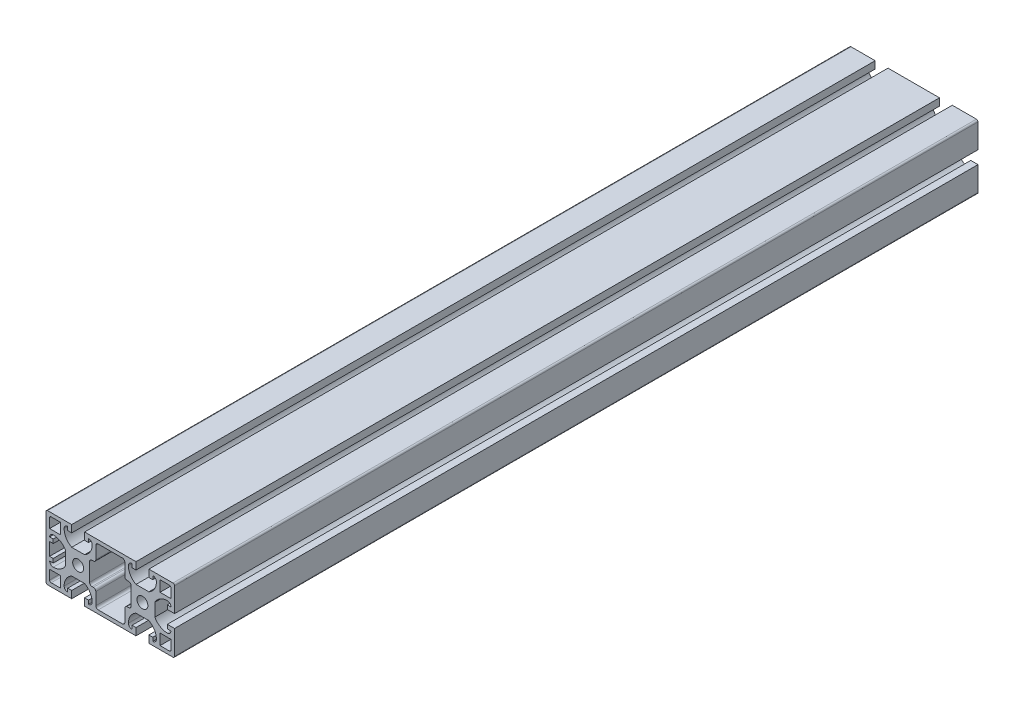
SolidWorks part; units mm, degrees
material "3.0255 (EN-AW 1350A)"
ref_plane "Płaszczyzna przednia" through (0, 0, 0) normal (0, 0, 1) x (1, 0, 0)
ref_plane "Płaszczyzna górna" through (0, 0, 0) normal (0, 1, 0) x (1, 0, 0)
ref_plane "Płaszczyzna prawa" through (0, 0, 0) normal (1, 0, 0) x (0, 0, -1)
sketch "Szkic1" plane through (0, 0, 0) normal (0, 0, 1) x (1, 0, 0)
  line L0 (0, 20) -> (0, -20) construction
  line L1 (-51.8865, 0) -> (40, 0) construction
  line L4 (-40, -19) -> (-40, 19)
  line L7 (-40, -20) -> (0, 0) construction
  line L8 (-40, 20) -> (40, -20) construction
  line L13 (20, 20) -> (20, 0) construction
  line L15 (24, 20) -> (24, 15.5)
  line L16 (24, 15.5) -> (26.4714, 15.5)
  line L21 (16, 15.5) -> (13.5286, 15.5)
  line L23 (16, 20) -> (13.5286, 20)
  line L24 (16, 20) -> (16, 15.5)
  line L25 (16, 7.75) -> (24, 7.75)
  line L26 (13.5286, 15.5) -> (13.5286, 17.75)
  line L27 (26.4714, 15.5) -> (26.4714, 17.75)
  line L28 (-24, 20) -> (-24, 15.5)
  line L29 (-26.4714, 15.5) -> (-26.4714, 17.75)
  line L30 (-24, 15.5) -> (-26.4714, 15.5)
  line L31 (-13.5286, 15.5) -> (-13.5286, 17.75)
  line L32 (-16, 15.5) -> (-13.5286, 15.5)
  line L33 (-16, 20) -> (-16, 15.5)
  line L34 (-16, 7.75) -> (-24, 7.75)
  line L35 (20, -20) -> (20, 0) construction
  line L36 (-40, -20) -> (0, 0) construction
  line L37 (-40, 20) -> (40, -20) construction
  line L38 (30.9714, -17.75) -> (36.75, -17.75)
  line L39 (-16, -7.75) -> (-24, -7.75)
  line L40 (-16, -20) -> (-16, -15.5)
  line L41 (-16, -15.5) -> (-13.5286, -15.5)
  line L42 (-13.5286, -15.5) -> (-13.5286, -17.75)
  line L43 (-24, -15.5) -> (-26.4714, -15.5)
  line L44 (-26.4714, -15.5) -> (-26.4714, -17.75)
  line L45 (-24, -20) -> (-24, -15.5)
  line L46 (26.4714, -15.5) -> (26.4714, -17.75)
  line L47 (13.5286, -15.5) -> (13.5286, -17.75)
  line L48 (16, -7.75) -> (24, -7.75)
  line L49 (16, -20) -> (16, -15.5)
  line L50 (16, -15.5) -> (13.5286, -15.5)
  line L51 (24, -15.5) -> (26.4714, -15.5)
  line L52 (24, -20) -> (24, -15.5)
  line L53 (40, -20) -> (0, 20) construction
  line L54 (35.5, 6.4714) -> (37.75, 6.4714)
  line L55 (35.5, 4) -> (35.5, 6.4714)
  line L56 (40, 4) -> (35.5, 4)
  line L57 (40, -4) -> (35.5, -4)
  line L58 (35.5, -4) -> (35.5, -6.4714)
  line L59 (35.5, -6.4714) -> (37.75, -6.4714)
  line L60 (27.75, 4) -> (27.75, -4)
  line L61 (-35.5, -6.4714) -> (-37.75, -6.4714)
  line L62 (-37.75, -4) -> (-35.5, -4)
  line L63 (-35.5, -4) -> (-35.5, -6.4714)
  line L64 (-35.5, 4) -> (-35.5, 6.4714)
  line L65 (-35.5, 6.4714) -> (-37.75, 6.4714)
  line L66 (-37.75, 4) -> (-35.5, 4)
  line L67 (-27.75, 4) -> (-27.75, -4)
  line L68 (-37.75, 4) -> (-37.75, -4)
  line L69 (40, -4) -> (40, -19)
  line L70 (40, 19) -> (40, 4)
  line L71 (-39, -20) -> (-24, -20)
  line L72 (-16, -20) -> (16, -20)
  line L73 (24, -20) -> (39, -20)
  line L74 (13.5286, 20) -> (-16, 20)
  line L75 (-24, 20) -> (-39, 20)
  line L76 (24, 20) -> (39, 20)
  line L77 (10.5286, 7.0902) -> (11.4095, 7.0902)
  line L78 (-7.5286, -17.75) -> (7.5286, -17.75)
  line L79 (-9.0286, -16.25) -> (-9.0286, -8.5902)
  line L80 (-7.5286, 17.75) -> (7.5286, 17.75)
  line L81 (9.0286, -16.25) -> (9.0286, -8.5902)
  line L82 (-9.0286, -17.75) -> (9.0286, 17.75) construction
  line L83 (-9.0286, 17.75) -> (9.0286, -17.75) construction
  line L84 (-11.4095, -7.0902) -> (-10.5286, -7.0902)
  line L85 (-12.9095, -5.5902) -> (-12.9095, 5.5902)
  line L86 (-11.4095, 7.0902) -> (-10.5286, 7.0902)
  line L87 (12.9095, -5.5902) -> (12.9095, 5.5902)
  line L88 (-12.9095, -7.0902) -> (0, 0) construction
  line L89 (-12.9095, 7.0902) -> (12.9095, -7.0902) construction
  line L90 (-9.0286, 8.5902) -> (-9.0286, 16.25)
  line L91 (-9.0286, 4.5143) -> (-9.0286, 4.9587)
  line L92 (-9.0286, -4.9587) -> (-9.0286, -4.5143)
  line L93 (9.0286, 8.5902) -> (9.0286, 16.25)
  line L94 (10.5286, -7.0902) -> (11.4095, -7.0902)
  line L96 (0, 0) -> (12.9095, 7.0902) construction
  line L98 (37.75, -10.9714) -> (37.75, -16.75)
  line L99 (30.9714, 10.9714) -> (37.75, 10.9714)
  line L100 (30.9714, 10.9714) -> (30.9714, 17.75)
  line L101 (30.9714, 17.75) -> (36.75, 17.75)
  line L102 (37.75, 10.9714) -> (37.75, 16.75)
  line L103 (30.9714, 10.9714) -> (37.75, 17.75) construction
  line L104 (30.9714, 17.75) -> (37.75, 10.9714) construction
  line L105 (30.9714, -10.9714) -> (37.75, -10.9714)
  line L106 (30.9714, -10.9714) -> (30.9714, -17.75)
  line L107 (-30.9714, -10.9714) -> (-30.9714, -17.75)
  line L108 (-30.9714, -10.9714) -> (-37.75, -10.9714)
  line L109 (-37.75, -10.9714) -> (-37.75, -16.75)
  line L110 (-30.9714, -17.75) -> (-36.75, -17.75)
  line L111 (-30.9714, 17.75) -> (-36.75, 17.75)
  line L112 (-37.75, 10.9714) -> (-37.75, 16.75)
  line L113 (-30.9714, 10.9714) -> (-37.75, 10.9714)
  line L114 (-30.9714, 10.9714) -> (-30.9714, 17.75)
  circle A0 centre (-20, 0) radius 3.4
  circle A1 centre (20, 0) radius 3.4
  arc A2 (26.4714, 17.75) -> (28.7214, 15.5) centre (26.4714, 15.5) cw
  arc A3 (28.7214, 15.5) -> (24, 7.75) centre (20, 15.5) cw
  arc A4 (13.5286, 17.75) -> (11.2786, 15.5) centre (13.5286, 15.5) ccw
  arc A5 (11.2786, 15.5) -> (16, 7.75) centre (20, 15.5) ccw
  arc A6 (-26.4714, 17.75) -> (-28.7214, 15.5) centre (-26.4714, 15.5) ccw
  arc A7 (-13.5286, 17.75) -> (-11.2786, 15.5) centre (-13.5286, 15.5) cw
  arc A8 (-11.2786, 15.5) -> (-16, 7.75) centre (-20, 15.5) cw
  arc A9 (-28.7214, 15.5) -> (-24, 7.75) centre (-20, 15.5) ccw
  arc A10 (-28.7214, -15.5) -> (-24, -7.75) centre (-20, -15.5) cw
  arc A11 (-11.2786, -15.5) -> (-16, -7.75) centre (-20, -15.5) ccw
  arc A12 (-13.5286, -17.75) -> (-11.2786, -15.5) centre (-13.5286, -15.5) ccw
  arc A13 (-26.4714, -17.75) -> (-28.7214, -15.5) centre (-26.4714, -15.5) cw
  arc A14 (11.2786, -15.5) -> (16, -7.75) centre (20, -15.5) cw
  arc A15 (13.5286, -17.75) -> (11.2786, -15.5) centre (13.5286, -15.5) cw
  arc A16 (28.7214, -15.5) -> (24, -7.75) centre (20, -15.5) ccw
  arc A17 (26.4714, -17.75) -> (28.7214, -15.5) centre (26.4714, -15.5) ccw
  arc A18 (35.5, 8.7214) -> (27.75, 4) centre (35.5, 0) ccw
  arc A19 (37.75, 6.4714) -> (35.5, 8.7214) centre (35.5, 6.4714) ccw
  arc A20 (37.75, -6.4714) -> (35.5, -8.7214) centre (35.5, -6.4714) cw
  arc A21 (35.5, -8.7214) -> (27.75, -4) centre (35.5, 0) cw
  arc A22 (-35.5, -8.7214) -> (-27.75, -4) centre (-35.5, 0) ccw
  arc A23 (-37.75, -6.4714) -> (-35.5, -8.7214) centre (-35.5, -6.4714) ccw
  arc A24 (-37.75, 6.4714) -> (-35.5, 8.7214) centre (-35.5, 6.4714) cw
  arc A25 (-35.5, 8.7214) -> (-27.75, 4) centre (-35.5, 0) cw
  arc A26 (-10.5286, 7.0902) -> (-9.0286, 8.5902) centre (-10.5286, 8.5902) ccw
  arc A27 (-9.0286, -8.5902) -> (-10.5286, -7.0902) centre (-10.5286, -8.5902) ccw
  arc A28 (11.4095, -7.0902) -> (12.9095, -5.5902) centre (11.4095, -5.5902) ccw
  arc A29 (9.0286, -8.5902) -> (10.5286, -7.0902) centre (10.5286, -8.5902) cw
  arc A30 (7.5286, -17.75) -> (9.0286, -16.25) centre (7.5286, -16.25) ccw
  arc A31 (-7.5286, -17.75) -> (-9.0286, -16.25) centre (-7.5286, -16.25) cw
  arc A32 (-11.4095, -7.0902) -> (-12.9095, -5.5902) centre (-11.4095, -5.5902) cw
  arc A33 (-12.9095, 5.5902) -> (-11.4095, 7.0902) centre (-11.4095, 5.5902) cw
  arc A34 (-9.0286, 16.25) -> (-7.5286, 17.75) centre (-7.5286, 16.25) cw
  arc A35 (7.5286, 17.75) -> (9.0286, 16.25) centre (7.5286, 16.25) cw
  arc A36 (11.4095, 7.0902) -> (12.9095, 5.5902) centre (11.4095, 5.5902) cw
  arc A37 (10.5286, 7.0902) -> (9.0286, 8.5902) centre (10.5286, 8.5902) cw
  arc A38 (-40, 19) -> (-39, 20) centre (-39, 19) cw
  arc A39 (-39, -20) -> (-40, -19) centre (-39, -19) cw
  arc A40 (39, -20) -> (40, -19) centre (39, -19) ccw
  arc A41 (39, 20) -> (40, 19) centre (39, 19) cw
  arc A42 (36.75, 17.75) -> (37.75, 16.75) centre (36.75, 16.75) cw
  arc A43 (36.75, -17.75) -> (37.75, -16.75) centre (36.75, -16.75) ccw
  arc A44 (-36.75, -17.75) -> (-37.75, -16.75) centre (-36.75, -16.75) cw
  arc A45 (-36.75, 17.75) -> (-37.75, 16.75) centre (-36.75, 16.75) ccw
  point P5 (0, 0)
  point P17 (0, 0)
  point P30 (24, 17.75)
  point P108 (0, 0)
  point P124 (-9.0286, 7.0902)
  point P132 (9.0286, -7.0902)
  point P156 (9.0286, 7.0902)
  point P161 (40, 20)
  point P162 (34.3607, 14.3607)
  dimension "D4" = 6.8
  dimension "D5" = 12.25
  dimension "D9" = 11
  dimension "D11" = 1.5
  dimension "D12" = 1
  dimension "D16" = 1
  dimension "D1" = 80
  dimension "D2" = 40
  dimension "D3" = 40
  dimension "D6" = 2.25
  dimension "D7" = 8
  dimension "D8" = 4.5
  dimension "D10" = 14.1804
  dimension "D13" = 2.25
  dimension "D14" = 2.25
  dimension "D15" = 2.25
extrude "Dodanie-wyciągnięcie1" add sketch "Szkic1" along normal blind 500 contours A20 A21 L60 A18 A19 L54 L55 L56 L70 L76 L15 L16 L27 A2 A3 L25 A5 A4 L26 L21 L24 L23 L74 L33 L32 L31 A7 A8 L34 A9 A6 L29 L30 L28 L75 L4 L71 L45 L43 L44 A13 A10 L39 A11 A12 L42 L41 L40 L72 L49 L50
